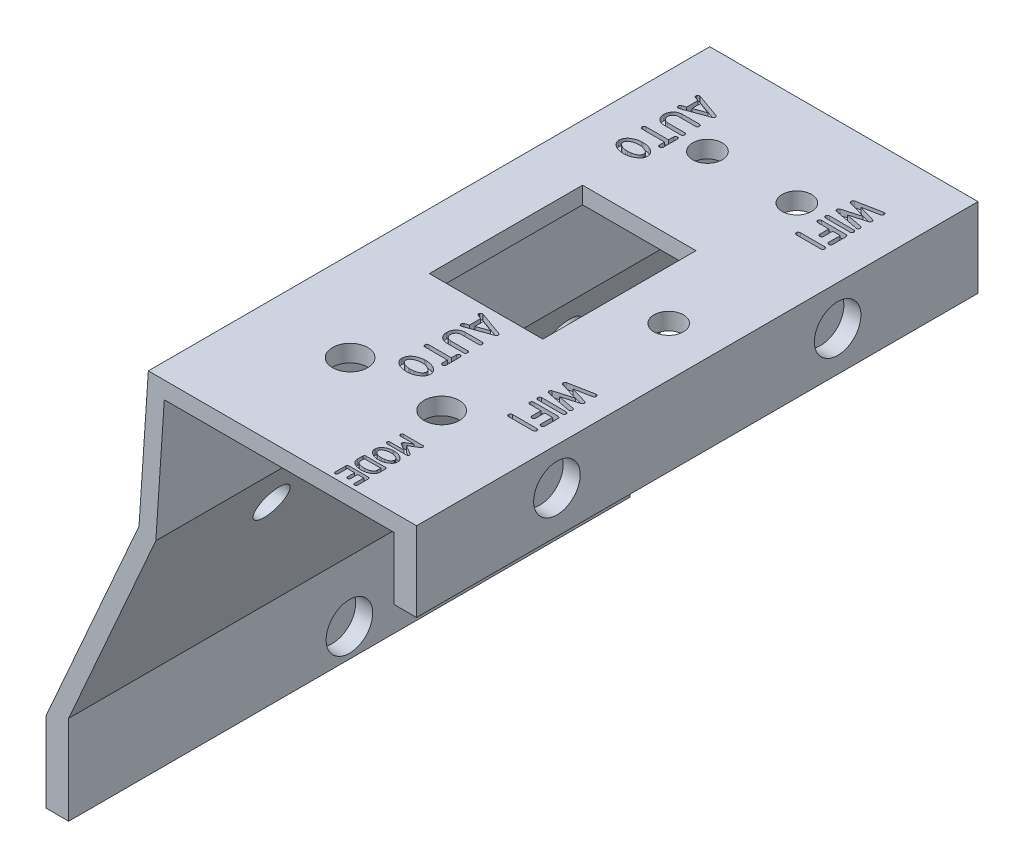
SolidWorks part; units mm, degrees
ref_plane "Plan de face" through (0, 0, 0) normal (0, 0, 1) x (1, 0, 0)
ref_plane "Plan de dessus" through (0, 0, 0) normal (0, 1, 0) x (1, 0, 0)
ref_plane "Plan de droite" through (0, 0, 0) normal (1, 0, 0) x (0, 0, -1)
sketch "Esquisse1" plane through (0, 0, -73.0547) normal (0, 0, -1) x (-1, 0, 0)
  line L8 (-48.2725, 208.1715) -> (285.0608, 208.1715) construction
  line L11 (-22.3565, 79.6481) -> (-22.3565, 93.6481)
  line L13 (-26.3565, 82.6481) -> (-79.1909, 82.6481) construction
  line L16 (-18.3565, 79.6481) -> (-18.3565, 90.6481)
  line L17 (-18.3565, 90.6481) -> (22.1017, 90.6481)
  line L20 (38.9454, 33.6107) -> (38.9454, 17.8931)
  line L22 (38.9454, 17.8931) -> (42.9454, 17.8931)
  line L23 (42.9454, 17.8931) -> (42.9454, 31.9959)
  line L26 (24.9144, 93.6481) -> (-22.3565, 93.6481)
  line L31 (38.9454, 33.6107) -> (23.5916, 68.3772)
  line L32 (22.8068, 80.1089) -> (25.8068, 80.3096) construction
  line L33 (30.9558, 51.702) -> (33.7063, 52.9167) construction
  line L34 (38.9454, 30.8508) -> (42.9454, 30.8508) construction
  line L36 (23.5916, 68.3772) -> (22.1017, 90.6481)
  line L46 (24.9144, 93.6481) -> (26.5563, 69.1069)
  line L49 (-22.3565, 79.6481) -> (-18.3565, 79.6481)
  line L51 (26.5563, 69.1069) -> (42.9454, 31.9959)
  dimension "D2" = 4
  dimension "D3" = 8
extrude "Boss.-Extru.1" add sketch "Esquisse1" along normal up to surface (14.7061 mm away) and the other way up to surface (84.2261 mm away)
sketch "Esquisse2" plane through (0, 93.6481, 0) normal (0, 1, 0) x (1, 0, 0)
  line L0 (3.0026, 53.4287) -> (-12.9974, 53.4287) construction
  line L1 (-14.9974, 55.4287) -> (5.0026, 55.4287)
  line L2 (-14.9974, 55.4287) -> (-14.9974, 28.4287)
  line L3 (-14.9974, 28.4287) -> (5.0026, 28.4287)
  line L4 (5.0026, 55.4287) -> (5.0026, 28.4287)
  line L5 (3.0026, 30.4287) -> (-12.9974, 30.4287) construction
  line L7 (3.0026, 30.9287) -> (3.0026, 30.4287) construction
  line L11 (-12.9974, 53.4287) -> (-12.9974, 52.9287) construction
  dimension "D1" = 2
  dimension "D2" = 2
  dimension "D3" = 2
  dimension "D4" = 2
extrude "Enlèv. mat.-Extru.1" cut sketch "Esquisse2" against normal up to next
sketch "Esquisse4" plane through (-14.9454, 0, 0) normal (-1, 0, 0) x (0, 0, 1)
  circle A0 centre (-63.9557, 60.6481) radius 3
  circle A1 centre (-12.6427, 60.6481) radius 3
  arc A2 (-61.0557, 60.6481) -> (-66.4557, 62.1178) centre (-63.9557, 60.6481) ccw construction
  arc A3 (-9.7427, 60.6481) -> (-15.1427, 62.1178) centre (-12.6427, 60.6481) ccw construction
  dimension "D1" = 6
extrude "Enlèv. mat.-Extru.3" cut sketch "Esquisse4" along normal up to next
sketch "Esquisse5" plane through (22.3565, 0, 0) normal (1, 0, 0) x (0, 0, -1)
  line L0 (38.2947, 93.6481) -> (38.2947, 79.6481) construction
  line L1 (87.7608, 79.6481) -> (-11.1713, 79.6481) construction
  line L2 (87.7608, 93.6481) -> (-11.1713, 93.6481) construction
  line L3 (-11.1706, 80.4126) -> (38.2947, 93.6481) construction
  line L4 (38.2947, 79.6481) -> (87.7608, 93.6481) construction
  circle A0 centre (13.562, 87.0304) radius 4.1
  circle A1 centre (63.0278, 86.6481) radius 4.1
  dimension "D1" = 8.2
extrude "Enlèv. mat.-Extru.4" cut sketch "Esquisse5" against normal blind 3
sketch "Esquisse6" plane through (-38.9454, 0, 0) normal (1, 0, 0) x (0, 0, -1)
  line L0 (-11.1713, 22.8931) -> (87.7608, 22.8931) construction
  line L1 (-11.1713, 33.6107) -> (-11.1713, 17.8931) construction
  line L2 (87.7608, 33.6107) -> (87.7608, 17.8931) construction
  line L3 (87.7608, 17.8931) -> (-11.1713, 17.8931) construction
  circle A0 centre (38.2947, 22.8931) radius 4.1
  dimension "D1" = 8.2
  dimension "D2" = 5
extrude "Enlèv. mat.-Extru.5" cut sketch "Esquisse6" against normal blind 3
sketch "Esquisse7" plane through (0, 93.6481, 0) normal (0, 1, 0) x (1, 0, 0)
  line L0 (-9.1574, 8.6287) -> (-24.9144, 8.6287) construction
  line L1 (-9.1574, 71.5948) -> (-24.9144, 71.5948) construction
  line L3 (-24.9144, 87.7608) -> (-24.9144, -11.1713) construction
  line L4 (6.9729, 8.6287) -> (22.3565, 8.6287) construction
  line L5 (22.3565, 87.7608) -> (22.3565, -11.1713) construction
  line L6 (-9.1574, 8.6287) -> (6.9729, 8.6287) construction
  line L7 (-1.0923, 28.4287) -> (-1.0923, -11.1713) construction
  line L9 (-24.9144, -11.1713) -> (22.3565, -11.1713) construction
  line L10 (6.5996, 71.5948) -> (22.3565, 71.5948) construction
  line L12 (-9.1574, 71.5948) -> (6.5996, 71.5948) construction
  line L13 (-1.2789, 87.7608) -> (-1.2789, 55.4287) construction
  line L14 (-24.9144, 87.7608) -> (22.3565, 87.7608) construction
  line L15 (5.0026, 55.4287) -> (-14.9974, 55.4287) construction
  line L16 (5.0026, 41.9287) -> (22.3565, 41.9287) construction
  line L17 (5.0026, 28.4287) -> (5.0026, 55.4287) construction
  line L18 (13.6796, -11.1713) -> (13.6796, 87.7608) construction
  circle A0 centre (-9.1574, 8.6287) radius 3.1
  circle A1 centre (6.9729, 8.6287) radius 3.1
  circle A3 centre (-9.1574, 71.5948) radius 2.6
  circle A4 centre (6.5996, 71.5948) radius 2.6
  circle A5 centre (13.6796, 41.9287) radius 2.6
  point P16 (-1.0923, 8.6287)
  point P17 (-1.0923, 8.6287)
  point P24 (-1.2789, 71.5948)
  point P25 (-1.2789, 71.5948)
  point P31 (13.6796, 41.9287)
  dimension "D1" = 6.2
  dimension "D3" = 5.2
  dimension "D2" = 16.1303
  dimension "D4" = 15.757
extrude "Enlèv. mat.-Extru.6" cut sketch "Esquisse7" against normal up to next
sketch "Esquisse8" plane through (0, 93.6481, 0) normal (0, 1, 0) x (1, 0, 0)
  line L0 (11.0996, 71.5948) -> (6.5996, 71.5948) construction
  line L1 (11.0996, 77.8229) -> (11.0996, 65.3667) construction
  line L2 (-9.1574, 71.5948) -> (-18.6574, 71.5948) construction
  line L3 (-18.6574, 63.2008) -> (-18.6574, 79.9888) construction
  line L4 (-4.5271, 26.3923) -> (-4.5271, 8.6287) construction
  line L5 (13.4729, 8.6287) -> (6.9729, 8.6287) construction
  line L6 (13.4729, 24.7222) -> (13.4729, 8.6287) construction
  line L7 (6.9729, 8.6287) -> (-4.5271, 8.6287) construction
  line L8 (6.9729, 8.6287) -> (6.9729, 1.6287) construction
  line L9 (6.9729, 1.6287) -> (6.9729, -9.0905) construction
  circle A0 centre (-9.1574, 71.5948) radius 2.6 construction
  circle A1 centre (6.9729, 8.6287) radius 7 construction
  text T0 "WIFI" font "MS 33558" height 5
  text T1 "AUTO" font "MS 33558" height 5
  text T2 "WIFI" font "MS 33558" height 5
  text T3 "AUTO" font "MS 33558" height 5
  text T4 "MODE" font "MS 33558" height 4
  dimension "D1" = 9.5
  dimension "D2" = 4.5
  dimension "D3" = 6.5
  dimension "D4" = 11.5
  dimension "D5" = 7
extrude "Enlèv. mat.-Extru.7" cut sketch "Esquisse8" against normal blind 1
